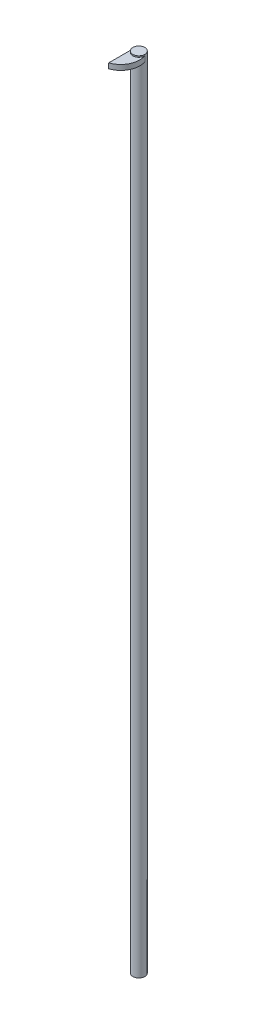
SolidWorks part; units mm, degrees
ref_plane "Front Plane" through (0, 0, 0) normal (0, 0, 1) x (1, 0, 0)
ref_plane "Top Plane" through (0, 0, 0) normal (0, 1, 0) x (1, 0, 0)
ref_plane "Right Plane" through (0, 0, 0) normal (1, 0, 0) x (0, 0, -1)
sketch "Sketch1" plane through (0, 4239.0773, 0) normal (0, 1, 0) x (1, 0, 0)
  circle A0 centre (838.8984, -1523.8201) radius 9.3137
extrude "Boss-Extrude1" add sketch "Sketch1" along normal blind 950 and the other way blind 286
sketch "Sketch2" plane through (0, 5189.0773, 0) normal (0, 1, 0) x (1, 0, 0)
  line L0 (829.5848, -1561.145) -> (829.5848, -1523.8201)
  line L1 (848.2121, -1523.8201) -> (829.5848, -1523.8201)
  arc A0 (848.2121, -1523.8201) -> (829.5848, -1561.145) centre (820.236, -1533.1689) cw
  circle A1 centre (838.8984, -1523.8201) radius 9.3137 construction
extrude "Boss-Extrude2" add sketch "Sketch2" against normal blind 5 and the other way blind 3 from offset 5
